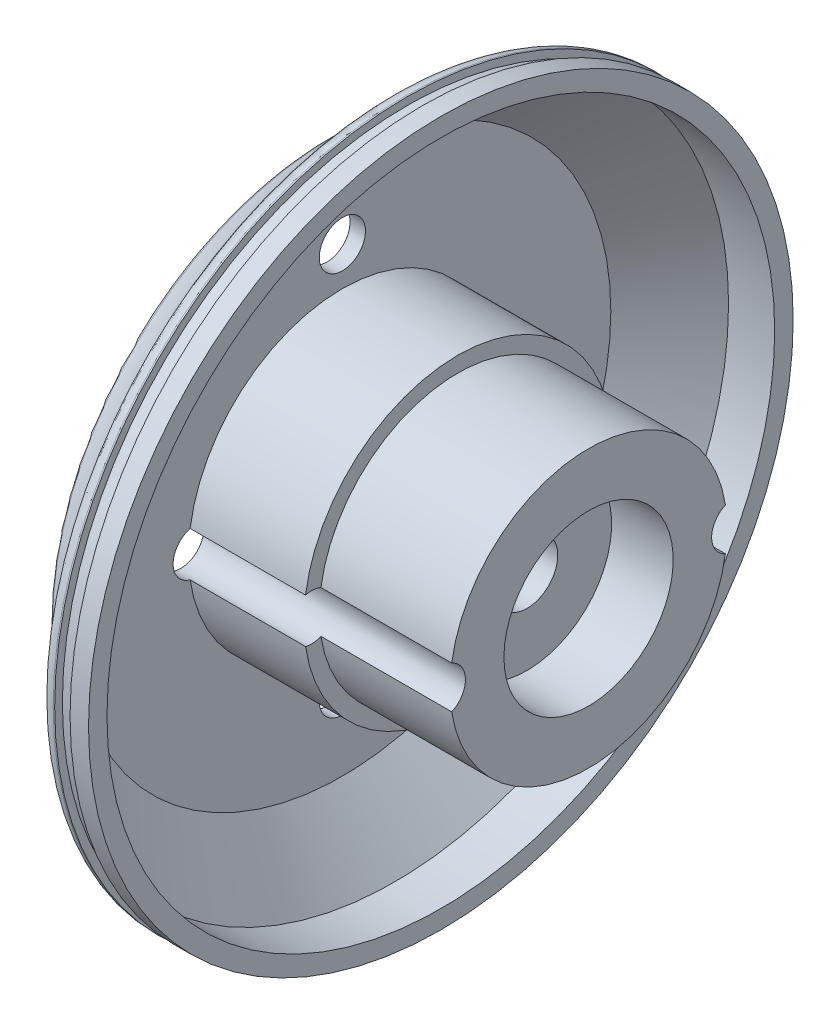
SolidWorks part; units mm, degrees
ref_plane "Front Plane" through (0, 0, 0) normal (0, 0, 1) x (1, 0, 0)
ref_plane "Top Plane" through (0, 0, 0) normal (0, 1, 0) x (1, 0, 0)
ref_plane "Right Plane" through (0, 0, 0) normal (1, 0, 0) x (0, 0, -1)
sketch "Sketch1" plane through (0, 0, 0) normal (0, 0, 1) x (1, 0, 0)
  line L0 (9.3645, 20.7387) -> (9.3645, -21.0613) construction
  line L1 (4, 2) -> (4, 5.5)
  line L2 (0, 5.5) -> (0, 18)
  line L3 (4.5, 22.9) -> (5.2, 22.9)
  line L4 (4.4, 21.7) -> (7.4, 21.7)
  line L5 (1, 10) -> (8.5, 10)
  line L6 (17, 9) -> (17, 5.5)
  line L7 (6.2, 22.9) -> (6.2, 22.4)
  line L8 (13, 2) -> (4, 2)
  line L9 (1, 17.4469) -> (4.4, 21.7)
  line L10 (7.4, 21.7) -> (7.4, 22.9)
  line L11 (1, 17.4469) -> (1, 10)
  line L12 (0, 0) -> (35.5, 0) construction
  line L13 (4, 5.5) -> (0, 5.5)
  line L14 (-37.6185, 20.7402) -> (-37.6185, 19.2402) construction
  line L15 (-37.6185, 15.1784) -> (-5.0714, 15.1784) construction
  line L16 (17, 9) -> (8.5, 9)
  line L17 (8.5, 9) -> (8.5, 10)
  line L18 (17, 5.5) -> (13, 5.5)
  line L19 (13, 5.5) -> (13, 2)
  line L20 (6.2, 22.4) -> (5.2, 22.4)
  line L21 (5.2, 22.4) -> (5.2, 22.9)
  line L22 (6.2, 22.9) -> (7.4, 22.9)
  arc A0 (0, 18) -> (4.5, 22.9) centre (-6.1834, 28.1949) ccw
  dimension "D4" = 9
  dimension "D1" = 41.8
  dimension "D2" = 35.5
  dimension "D3" = 1.5
  dimension "D5" = 1.2
  dimension "D6" = 18
  dimension "D7" = 5.5
  dimension "D8" = 10
  dimension "D9" = 1
  dimension "D10" = 4.5
  dimension "D11" = 3
  dimension "D12" = 1.2
  dimension "D13" = 4
  dimension "D14" = 22.9
  dimension "D15" = 4.5
  dimension "D16" = 0.5
  dimension "D17" = 17
  dimension "D18" = 2
  dimension "D19" = 1
  dimension "D20" = 0.7
revolve "Revolve1" add sketch "Sketch1" angle 360 about L12
fillet "Fillet1" radius 1 2 edges at (4.5, 0, 22.9) (0, 0, 18)
sketch "Sketch3" plane through (0, 0, 0) normal (-1, 0, 0) x (0, 0, 1)
  line L0 (0, 0) -> (0, 18.5597) construction
  line L1 (0, 0) -> (-18.673, 18.673) construction
  line L2 (0, 0) -> (16.4085, 16.4085) construction
  line L3 (0, 0) -> (6.2748, 0) construction
  arc A0 (-7.1621, 21.7512) -> (7.1621, 21.7512) centre (0, 0) cw
  circle A1 centre (0, 0) radius 22.9 construction
  arc A2 (10.316, 20.4448) -> (20.4448, 10.316) centre (0, 0) cw
  arc A3 (21.7512, 7.1621) -> (21.7512, -7.1621) centre (0, 0) cw
  arc A4 (20.4448, -10.316) -> (10.316, -20.4448) centre (0, 0) cw
  arc A5 (6.8027, -4.2099) -> (13.6053, -8.4199) centre (10.204, -6.3149) cw
  arc A6 (6.8027, -4.2099) -> (4.2099, -6.8027) centre (0, 0) cw
  arc A7 (4.2099, -6.8027) -> (8.4199, -13.6053) centre (6.3149, -10.204) ccw
  arc A8 (13.6053, -8.4199) -> (8.4199, -13.6053) centre (0, 0) cw
  arc A9 (-4.2099, -6.8027) -> (-8.4199, -13.6053) centre (-6.3149, -10.204) cw
  arc A10 (-4.2099, -6.8027) -> (-6.8027, -4.2099) centre (0, 0) cw
  arc A17 (-6.8027, -4.2099) -> (-13.6053, -8.4199) centre (-10.204, -6.3149) ccw
  arc A18 (-8.4199, -13.6053) -> (-13.6053, -8.4199) centre (0, 0) cw
  arc A19 (-6.8027, 4.2099) -> (-13.6053, 8.4199) centre (-10.204, 6.3149) cw
  arc A20 (-6.8027, 4.2099) -> (-4.2099, 6.8027) centre (0, 0) cw
  arc A21 (-4.2099, 6.8027) -> (-8.4199, 13.6053) centre (-6.3149, 10.204) ccw
  arc A22 (7.1621, -21.7512) -> (-7.1621, -21.7512) centre (0, 0) cw
  arc A23 (-13.6053, 8.4199) -> (-8.4199, 13.6053) centre (0, 0) cw
  arc A24 (-10.316, -20.4448) -> (-20.4448, -10.316) centre (0, 0) cw
  arc A25 (-21.7512, -7.1621) -> (-21.7512, 7.1621) centre (0, 0) cw
  arc A26 (-20.4448, 10.316) -> (-10.316, 20.4448) centre (0, 0) cw
  arc A29 (4.2099, 6.8027) -> (6.8027, 4.2099) centre (0, 0) cw
  arc A30 (8.4199, 13.6053) -> (13.6053, 8.4199) centre (0, 0) cw
  arc A31 (4.2099, 6.8027) -> (8.4199, 13.6053) centre (6.3149, 10.204) cw
  arc A32 (6.8027, 4.2099) -> (13.6053, 8.4199) centre (10.204, 6.3149) ccw
  circle A37 centre (0, 12.5) radius 1.5
  circle A38 centre (-9.5, 0) radius 1.5
  circle A39 centre (9.5, 0) radius 1.5
  circle A40 centre (0, -12.5) radius 1.5
  ellipse E0 centre (0, 29.4609) end of major axis (0, 17.0494) minor radius 9.1392 (-7.1621, 21.7512) -> (7.1621, 21.7512) ccw
  ellipse E1 centre (20.832, 20.832) end of major axis (12.2999, 12.2999) minor radius 9.3106 (10.316, 20.4448) -> (20.4448, 10.316) ccw
  ellipse E2 centre (29.4609, 0) end of major axis (17.3947, 0) minor radius 9.3106 (21.7512, 7.1621) -> (21.7512, -7.1621) ccw
  ellipse E3 centre (20.832, -20.832) end of major axis (12.2999, -12.2999) minor radius 9.3106 (20.4448, -10.316) -> (10.316, -20.4448) ccw
  ellipse E4 centre (0, -29.4609) end of major axis (0, -17.3947) minor radius 9.3106 (7.1621, -21.7512) -> (-7.1621, -21.7512) ccw
  ellipse E5 centre (-20.832, -20.832) end of major axis (-12.2999, -12.2999) minor radius 9.3106 (-10.316, -20.4448) -> (-20.4448, -10.316) ccw
  ellipse E6 centre (-29.4609, 0) end of major axis (-17.3947, 0) minor radius 9.3106 (-21.7512, -7.1621) -> (-21.7512, 7.1621) ccw
  ellipse E7 centre (-20.832, 20.832) end of major axis (-29.6083, 29.6083) minor radius 9.1392 (-20.4448, 10.316) -> (-10.316, 20.4448) ccw
  point P36 (0, 0)
  point P74 (0, 0)
  point P80 (0, 0)
  point P140 (0, 0)
  dimension "D2" = 8
  dimension "D4" = 4
  dimension "D6" = 16
  dimension "D8" = 5.5
  dimension "D12" = 3
  dimension "D3" = 45
  dimension "D7" = 45
  dimension "D13" = 25
  dimension "D14" = 19
  dimension "D5" = 8
chamfer "Chamfer2" [suppressed] distance 0.5 angle 45
extrude "Cut-Extrude2" cut sketch "Sketch3" against normal through all contours A38 | A37 | A39 | A40
